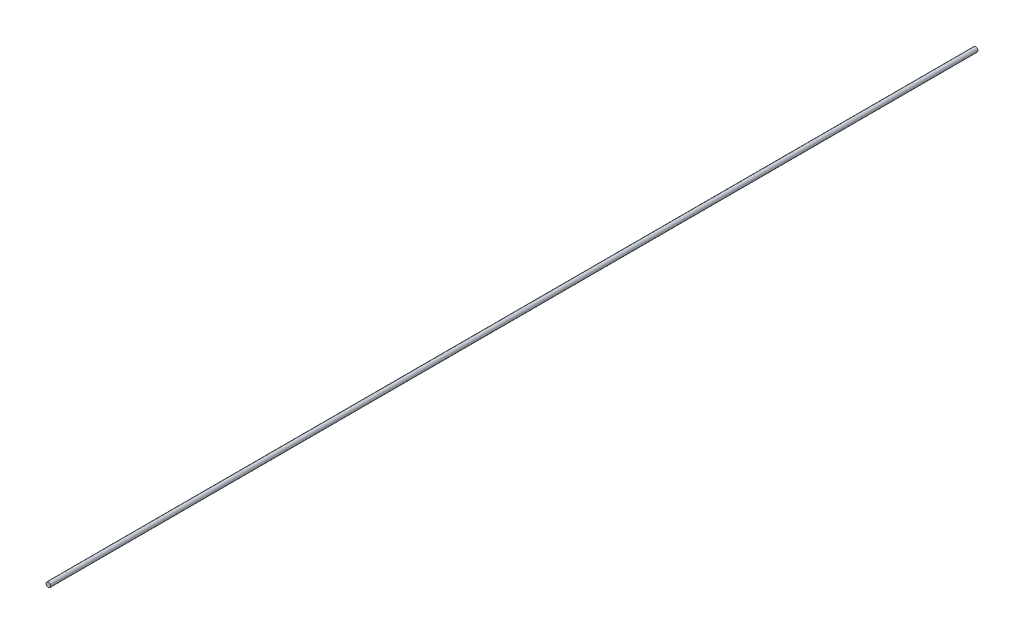
SolidWorks part; units mm, degrees
ref_plane "Front Plane" through (0, 0, 0) normal (0, 0, 1) x (1, 0, 0)
ref_plane "Top Plane" through (0, 0, 0) normal (0, 1, 0) x (1, 0, 0)
ref_plane "Right Plane" through (0, 0, 0) normal (1, 0, 0) x (0, 0, -1)
sketch "Sketch1" plane through (0, 0, 0) normal (0, 0, 1) x (1, 0, 0)
  circle A0 centre (0, 0) radius 3.175
  dimension "D1" = 6.35
extrude "Boss-Extrude1" add sketch "Sketch1" along normal blind 1270
